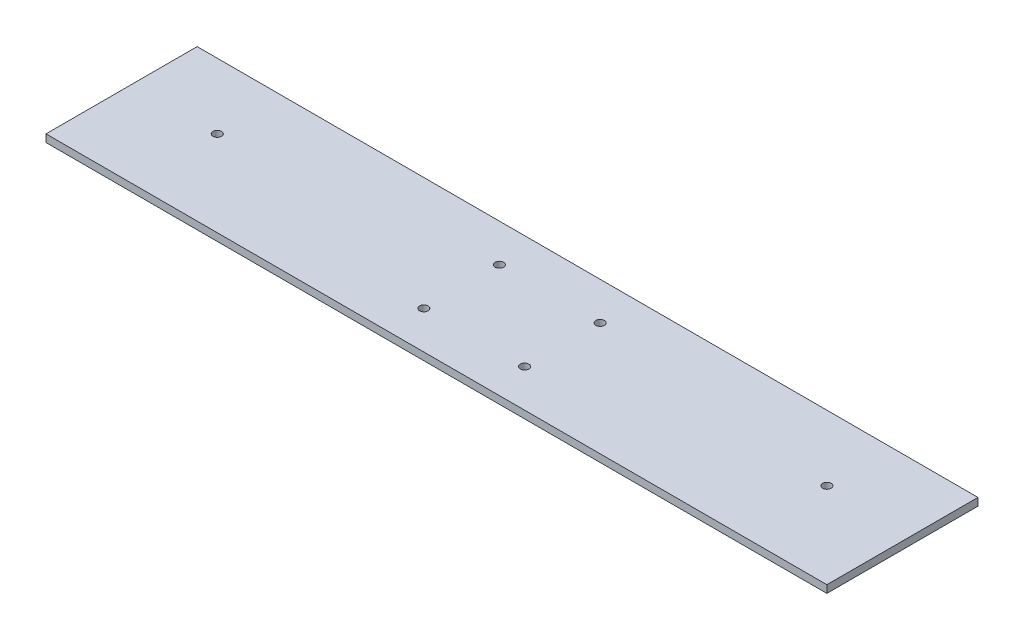
SolidWorks part; units mm, degrees
ref_plane "Płaszczyzna przednia" through (0, 0, 0) normal (0, 0, 1) x (1, 0, 0)
ref_plane "Płaszczyzna górna" through (0, 0, 0) normal (0, 1, 0) x (1, 0, 0)
ref_plane "Płaszczyzna prawa" through (0, 0, 0) normal (1, 0, 0) x (0, 0, -1)
sketch "Sketch1" plane through (0, 0, 0) normal (0, 1, 0) x (1, 0, 0)
  line L1 (-10, 0) -> (300, 0)
  line L2 (-10, 0) -> (-10, 60)
  line L3 (-10, 60) -> (300, 60)
  line L4 (300, 0) -> (300, 60)
  dimension "D1" = 310
  dimension "D2" = 60
extrude "Boss-Extrude1" add sketch "Sketch1" along normal blind 3
hole_wizard "Otwór pod śrubę M31" positions "Sketch2" profile "Sketch3" hole size "M3" standard "Ansi Metric" end condition through all
sketch "Sketch2" plane through (0, 3, 0) normal (0, 1, 0) x (1, 0, 0)
  line L0 (-10, 60) -> (-10, 0) construction
  line L1 (-10, 0) -> (300, 0) construction
  line L2 (300, 0) -> (300, 60) construction
  line L3 (300, 60) -> (-10, 60) construction
  point P0 (266, 34)
  point P2 (24, 34)
  point P20 (125, 15)
  point P22 (165, 15)
  point P24 (165, 45)
  point P26 (125, 45)
  point P37 (0, 0)
  point P38 (0, 0)
  point P39 (0, 0)
  point P40 (0, 0)
  point P41 (0, 0)
  point P42 (0, 0)
  point P43 (0, 0)
  point P44 (0, 0)
  dimension "D1" = 34
  dimension "D2" = 34
  dimension "D3" = 34
  dimension "D4" = 34
  dimension "D11" = 15
  dimension "D12" = 15
  dimension "D15" = 15
  dimension "D16" = 15
  dimension "D25" = 40
  dimension "D26" = 40
  dimension "D27" = 135
  dimension "D28" = 135
sketch "Sketch3" plane through (266, 3, -34) normal (1, 0, 0) x (0, 0, 1)
  line L0 (0, 0) -> (0, 3)
  line L1 (0, 3) -> (1.7, 3)
  line L2 (1.7, 3) -> (1.7, 0)
  line L5 (1.7, 0) -> (0, 0)
  line L11 (0, -6.35) -> (0, 107.95) construction
  dimension "Œrednica otworu na wylot" = 3.4
  dimension "G³êbokoœæ otworu na wylot" = 3
